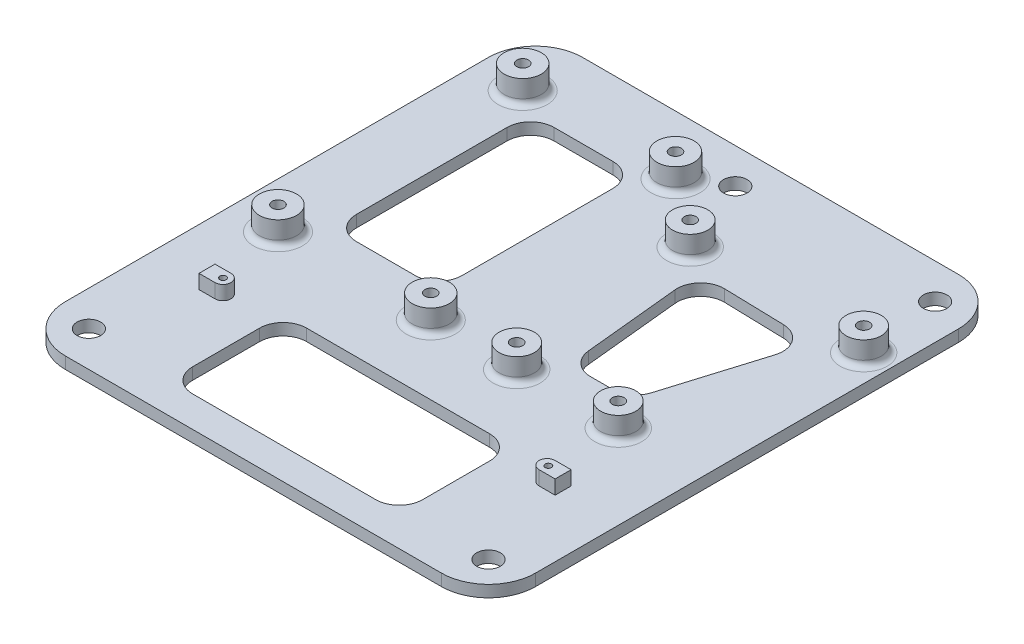
SolidWorks part; units mm, degrees
ref_plane "Front Plane" through (0, 0, 0) normal (0, 0, 1) x (1, 0, 0)
ref_plane "Top Plane" through (0, 0, 0) normal (0, 1, 0) x (1, 0, 0)
ref_plane "Right Plane" through (0, 0, 0) normal (1, 0, 0) x (0, 0, -1)
sketch "Sketch1" plane through (0, 0, 0) normal (0, 1, 0) x (1, 0, 0)
  line L0 (9.525, -85.09) -> (149.5329, -85.09) construction
  line L1 (0, 0) -> (127, 0) construction
  line L2 (0, 0) -> (0, -139.7) construction
  line L3 (0, -139.7) -> (127, -139.7) construction
  line L4 (127, 0) -> (127, -139.7) construction
  line L6 (15.24, -101.8159) -> (15.24, -106.1339)
  line L8 (111.4298, -101.8159) -> (111.4298, -106.1339)
  line L9 (9.525, -12.7) -> (56.515, -12.7) construction
  line L10 (9.525, -12.7) -> (9.525, -85.09) construction
  line L11 (9.525, -85.09) -> (56.515, -85.09) construction
  line L12 (56.515, -12.7) -> (56.515, -85.09) construction
  line L13 (117.475, -85.09) -> (69.215, -85.09) construction
  line L14 (117.475, -85.09) -> (117.475, -11.43) construction
  line L16 (69.215, -85.09) -> (69.215, -11.43) construction
  line L17 (15.24, -106.1339) -> (19.558, -106.1339) construction
  line L18 (15.24, -101.8159) -> (19.558, -101.8159) construction
  line L19 (107.1118, -101.8159) -> (111.4298, -101.8159) construction
  line L20 (111.4298, -101.8159) -> (107.1118, -101.8159)
  line L21 (111.4298, -101.8159) -> (111.4298, -106.1339)
  line L22 (111.4298, -106.1339) -> (107.1118, -106.1339)
  line L24 (15.24, -101.8159) -> (19.558, -101.8159)
  line L25 (15.24, -101.8159) -> (15.24, -106.1339)
  line L26 (15.24, -106.1339) -> (19.558, -106.1339)
  line L28 (107.1118, -106.1339) -> (111.4298, -106.1339) construction
  line L29 (76.835, -81.915) -> (104.267, -81.915) construction
  line L30 (12.3825, -15.8433) -> (53.6575, -15.8433) construction
  line L31 (12.3825, -15.8433) -> (12.3825, -81.9468) construction
  line L32 (12.3825, -81.9468) -> (53.6575, -81.9468) construction
  line L33 (53.6575, -15.8433) -> (53.6575, -81.9468) construction
  line L34 (71.628, -29.845) -> (119.761, -31.115) construction
  line L35 (12.7, 0) -> (114.3, 0)
  line L36 (0, -12.7) -> (0, -127)
  line L37 (12.7, -139.7) -> (114.3, -139.7)
  line L38 (127, -12.7) -> (127, -127)
  line L39 (25.0825, -22.1933) -> (40.9575, -22.1933)
  line L40 (18.7325, -28.5433) -> (18.7325, -69.2467)
  line L41 (25.0825, -75.5968) -> (40.9575, -75.5968)
  line L42 (47.3075, -28.5433) -> (47.3075, -69.2467)
  line L43 (119.761, -31.115) -> (104.267, -81.915) construction
  line L44 (104.267, -81.915) -> (76.835, -81.915) construction
  line L45 (76.835, -81.915) -> (71.628, -29.845) construction
  line L46 (85.8998, -36.9074) -> (102.2124, -37.3378)
  line L47 (108.1187, -45.5381) -> (100.3322, -71.0675)
  line L48 (94.2584, -75.565) -> (88.3283, -75.565)
  line L49 (82.0099, -69.8468) -> (79.4139, -43.887)
  line L51 (38.608, -102.5586) -> (88.0618, -102.5586)
  line L52 (32.258, -108.9086) -> (32.258, -127)
  line L53 (38.608, -133.35) -> (88.0618, -133.35)
  line L54 (94.4118, -108.9086) -> (94.4118, -127)
  arc A0 (19.558, -106.1339) -> (19.558, -101.8159) centre (19.558, -103.9749) ccw
  arc A1 (107.1118, -101.8159) -> (107.1118, -106.1339) centre (107.1118, -103.9749) ccw
  circle A3 centre (12.3825, -15.8433) radius 5.0165
  circle A5 centre (53.6575, -15.8433) radius 5.0165
  circle A7 centre (12.3825, -81.9468) radius 5.0165
  circle A9 centre (53.6575, -81.9468) radius 5.0165
  circle A10 centre (71.628, -29.845) radius 1.5875
  circle A11 centre (71.628, -29.845) radius 4.7625
  circle A12 centre (76.835, -81.915) radius 1.5875
  circle A13 centre (76.835, -81.915) radius 4.7625
  circle A14 centre (104.267, -81.915) radius 1.5875
  circle A15 centre (104.267, -81.915) radius 4.7625
  circle A16 centre (119.761, -31.115) radius 1.5875
  circle A17 centre (119.761, -31.115) radius 4.7625
  circle A18 centre (53.6575, -15.8433) radius 1.5875
  circle A19 centre (12.3825, -15.8433) radius 1.5875
  circle A20 centre (12.3825, -81.9468) radius 1.5875
  circle A21 centre (53.6575, -81.9468) radius 1.5875
  arc A22 (0, -127) -> (12.7, -139.7) centre (12.7, -127) ccw
  arc A23 (114.3, -139.7) -> (127, -127) centre (114.3, -127) ccw
  arc A24 (114.3, 0) -> (127, -12.7) centre (114.3, -12.7) cw
  arc A25 (12.7, 0) -> (0, -12.7) centre (12.7, -12.7) ccw
  arc A26 (40.9575, -75.5968) -> (47.3075, -69.2467) centre (40.9575, -69.2468) ccw
  arc A27 (18.7325, -69.2467) -> (25.0825, -75.5968) centre (25.0825, -69.2468) ccw
  arc A28 (25.0825, -22.1933) -> (18.7325, -28.5433) centre (25.0825, -28.5433) ccw
  arc A29 (40.9575, -22.1933) -> (47.3075, -28.5433) centre (40.9575, -28.5433) cw
  arc A30 (38.608, -102.5586) -> (32.258, -108.9086) centre (38.608, -108.9086) ccw
  arc A31 (32.258, -127) -> (38.608, -133.35) centre (38.608, -127) ccw
  arc A32 (88.0618, -133.35) -> (94.4118, -127) centre (88.0618, -127) ccw
  arc A33 (88.0618, -102.5586) -> (94.4118, -108.9086) centre (88.0618, -108.9086) cw
  arc A34 (85.8998, -36.9074) -> (79.4139, -43.887) centre (85.7324, -43.2552) ccw
  arc A35 (102.2124, -37.3378) -> (108.1187, -45.5381) centre (102.0449, -43.6856) cw
  arc A36 (100.3322, -71.0675) -> (94.2584, -75.565) centre (94.2584, -69.215) cw
  arc A37 (88.3283, -75.565) -> (82.0099, -69.8468) centre (88.3283, -69.215) cw
  point P76 (74.2315, -55.88)
  dimension "D18" = 2.159
  dimension "D19" = 2.159
  dimension "D21" = 2.413
  dimension "D22" = 10.033
  dimension "D26" = 52.07
  dimension "D27" = 12.7
  dimension "D30" = 6.35
  dimension "D32" = 6.35
  dimension "D41" = 6.35
  dimension "D1" = 127
  dimension "D2" = 139.7
  dimension "D3" = 33.5661
  dimension "D4" = 96.1898
  dimension "D5" = 15.24
  dimension "D6" = 41.275
  dimension "D7" = 46.99
  dimension "D8" = 72.39
  dimension "D9" = 9.525
  dimension "D10" = 66.1035
  dimension "D11" = 48.133
  dimension "D12" = 1.27
  dimension "D13" = 9.525
  dimension "D14" = 3.1433
  dimension "D15" = 4.318
  dimension "D16" = 4.318
  dimension "D17" = 4.318
  dimension "D20" = 2.8575
  dimension "D23" = 27.432
  dimension "D24" = 7.62
  dimension "D25" = 3.175
  dimension "D28" = 6.35
  dimension "D29" = 6.35
  dimension "D31" = 6.35
  dimension "D33" = 0
  dimension "D34" = 6.35
  dimension "D35" = 0
  dimension "D36" = 0
  dimension "D37" = 6.35
  dimension "D38" = 6.35
  dimension "D39" = 12.7
  dimension "D40" = 12.7
extrude "Boss-Extrude5" add sketch "Sketch1" along normal blind 3.175 contours L37 A23 L38 A24 L35 A25 L36 A22
sketch "Sketch2" plane through (0, 3.175, 0) normal (0, 1, 0) x (1, 0, 0)
  line L0 (15.24, -106.1339) -> (15.24, -101.8159)
  line L1 (15.24, -101.8159) -> (19.558, -101.8159)
  line L2 (15.24, -106.1339) -> (19.558, -106.1339)
  line L3 (107.1118, -101.8159) -> (111.4298, -101.8159)
  line L4 (111.4298, -101.8159) -> (111.4298, -106.1339)
  line L5 (111.4298, -106.1339) -> (107.1118, -106.1339)
  circle A0 centre (12.3825, -15.8433) radius 5.0165
  circle A1 centre (53.6575, -15.8433) radius 5.0165
  circle A2 centre (71.628, -29.845) radius 4.7625
  circle A3 centre (119.761, -31.115) radius 4.7625
  circle A4 centre (104.267, -81.915) radius 4.7625
  circle A5 centre (76.835, -81.915) radius 4.7625
  circle A6 centre (53.6575, -81.9468) radius 5.0165
  circle A7 centre (12.3825, -81.9468) radius 5.0165
  circle A8 centre (12.3825, -15.8433) radius 1.5875
  circle A9 centre (53.6575, -15.8433) radius 1.5875
  circle A10 centre (71.628, -29.845) radius 1.5875
  circle A11 centre (119.761, -31.115) radius 1.5875
  circle A12 centre (104.267, -81.915) radius 1.5875
  circle A13 centre (76.835, -81.915) radius 1.5875
  circle A14 centre (53.6575, -81.9468) radius 1.5875
  circle A15 centre (12.3825, -81.9468) radius 1.5875
  arc A16 (19.558, -106.1339) -> (19.558, -101.8159) centre (19.558, -103.9749) ccw
  arc A17 (107.1118, -101.8159) -> (107.1118, -106.1339) centre (107.1118, -103.9749) ccw
  dimension "D1" = 3.175
extrude "Boss-Extrude6" add sketch "Sketch2" along normal blind 6.35
sketch "Sketch3" plane through (0, 9.525, 0) normal (0, 1, 0) x (1, 0, 0)
  line L0 (19.558, -101.8159) -> (15.24, -101.8159)
  line L1 (15.24, -101.8159) -> (15.24, -106.1339)
  line L2 (15.24, -106.1339) -> (19.558, -106.1339)
  line L3 (63.5, -139.7) -> (63.5, 0) construction
  line L4 (12.7, -139.7) -> (114.3, -139.7) construction
  line L5 (12.7, 0) -> (114.3, 0) construction
  line L9 (111.4298, -101.8159) -> (111.4298, -106.1339)
  line L10 (111.4298, -106.1339) -> (107.1118, -106.1339)
  line L11 (107.1118, -101.8159) -> (111.4298, -101.8159)
  arc A0 (19.558, -106.1339) -> (19.558, -101.8159) centre (19.558, -103.9749) ccw
  arc A1 (107.1118, -101.8159) -> (107.1118, -106.1339) centre (107.1118, -103.9749) ccw
extrude "Cut-Extrude1" cut sketch "Sketch3" against normal blind 2.54
sketch "Sketch4" plane through (0, 0, 0) normal (0, -1, 0) x (1, 0, 0)
  line L12 (127, 69.85) -> (0, 69.85) construction
  line L13 (127, 12.7) -> (127, 127) construction
  line L14 (0, 12.7) -> (0, 127) construction
  line L15 (32.4233, 106.9507) -> (32.4233, 125.0421)
  line L16 (38.7733, 131.3921) -> (88.2271, 131.3921)
  line L17 (94.5771, 106.9507) -> (94.5771, 125.0421)
  line L18 (38.7733, 100.6007) -> (88.2271, 100.6007)
  line L19 (82.1752, 67.889) -> (79.5792, 41.9291)
  line L20 (94.4237, 73.6071) -> (88.4937, 73.6071)
  line L21 (108.284, 43.5802) -> (100.4975, 69.1096)
  line L22 (86.0652, 34.9495) -> (102.3777, 35.3799)
  line L23 (18.8978, 26.5854) -> (18.8978, 67.2889)
  line L24 (25.2478, 73.6389) -> (41.1228, 73.6389)
  line L25 (47.4728, 26.5854) -> (47.4728, 67.2889)
  line L26 (25.2478, 20.2354) -> (41.1228, 20.2354)
  line L27 (63.5, 0) -> (63.5, 139.7) construction
  line L28 (12.7, 0) -> (114.3, 0) construction
  line L29 (12.7, 139.7) -> (114.3, 139.7) construction
  line L30 (38.7733, 125.0421) -> (88.2271, 106.9507) construction
  line L31 (88.2271, 125.0421) -> (38.7733, 106.9507) construction
  line L33 (9.525, 9.525) -> (117.475, 9.525) construction
  line L34 (9.525, 9.525) -> (9.525, 130.175) construction
  line L35 (9.525, 130.175) -> (117.475, 130.175) construction
  line L36 (117.475, 9.525) -> (117.475, 130.175) construction
  arc A12 (38.7733, 100.6007) -> (32.4233, 106.9507) centre (38.7733, 106.9507) cw
  arc A13 (32.4233, 125.0421) -> (38.7733, 131.3921) centre (38.7733, 125.0421) cw
  arc A14 (88.2271, 131.3921) -> (94.5771, 125.0421) centre (88.2271, 125.0421) cw
  arc A15 (88.2271, 100.6007) -> (94.5771, 106.9507) centre (88.2271, 106.9507) ccw
  arc A16 (86.0652, 34.9495) -> (79.5792, 41.9291) centre (85.8977, 41.2973) cw
  arc A17 (88.4937, 73.6071) -> (82.1752, 67.889) centre (88.4937, 67.2571) ccw
  arc A18 (100.4975, 69.1096) -> (94.4237, 73.6071) centre (94.4237, 67.2571) ccw
  arc A19 (102.3777, 35.3799) -> (108.284, 43.5802) centre (102.2102, 41.7277) ccw
  arc A20 (25.2478, 20.2354) -> (18.8978, 26.5854) centre (25.2478, 26.5854) cw
  arc A21 (18.8978, 67.2889) -> (25.2478, 73.6389) centre (25.2478, 67.2889) cw
  arc A22 (41.1228, 73.6389) -> (47.4728, 67.2889) centre (41.1228, 67.2889) cw
  arc A23 (41.1228, 20.2354) -> (47.4728, 26.5854) centre (41.1228, 26.5854) ccw
  circle A27 centre (117.475, 130.175) radius 3.175
  circle A28 centre (12.7, 12.7) radius 12.7 construction
  circle A29 centre (117.475, 9.525) radius 3.175
  circle A31 centre (9.525, 130.175) radius 3.175
  circle A33 centre (63.5, 9.525) radius 3.175
  dimension "D1" = 6.35
  dimension "D2" = 9.525
  dimension "D3" = 9.525
  dimension "D4" = 9.525
  dimension "D5" = 9.525
extrude "Cut-Extrude2" cut sketch "Sketch4" against normal up to surface (3.175 mm away) up to face at (12.3825, 3.175, 86.9633)
fillet "Fillet1" radius 1.5875 8 edges at (104.267, 3.175, 86.6775) (119.761, 3.175, 35.8775) (71.628, 3.175, 34.6075) (76.835, 3.175, 86.6775) (53.6575, 3.175, 86.9633) (53.6575, 3.175, 20.8598) (12.3825, 3.175, 20.8598) (12.3825, 3.175, 86.9633)
sketch "Sketch5" plane through (0, 6.985, 0) normal (0, 1, 0) x (1, 0, 0)
  line L0 (63.5002, -131.3921) -> (63.5002, -100.6007) construction
  line L1 (88.2271, -131.3921) -> (38.7733, -131.3921) construction
  line L2 (38.7733, -100.6007) -> (88.2271, -100.6007) construction
  circle A0 centre (19.558, -103.9749) radius 2.159 construction
  circle A2 centre (107.4424, -103.9749) radius 0.8509
  circle A3 centre (19.558, -103.9749) radius 0.8509
extrude "Cut-Extrude3" cut sketch "Sketch5" against normal blind 6.35
